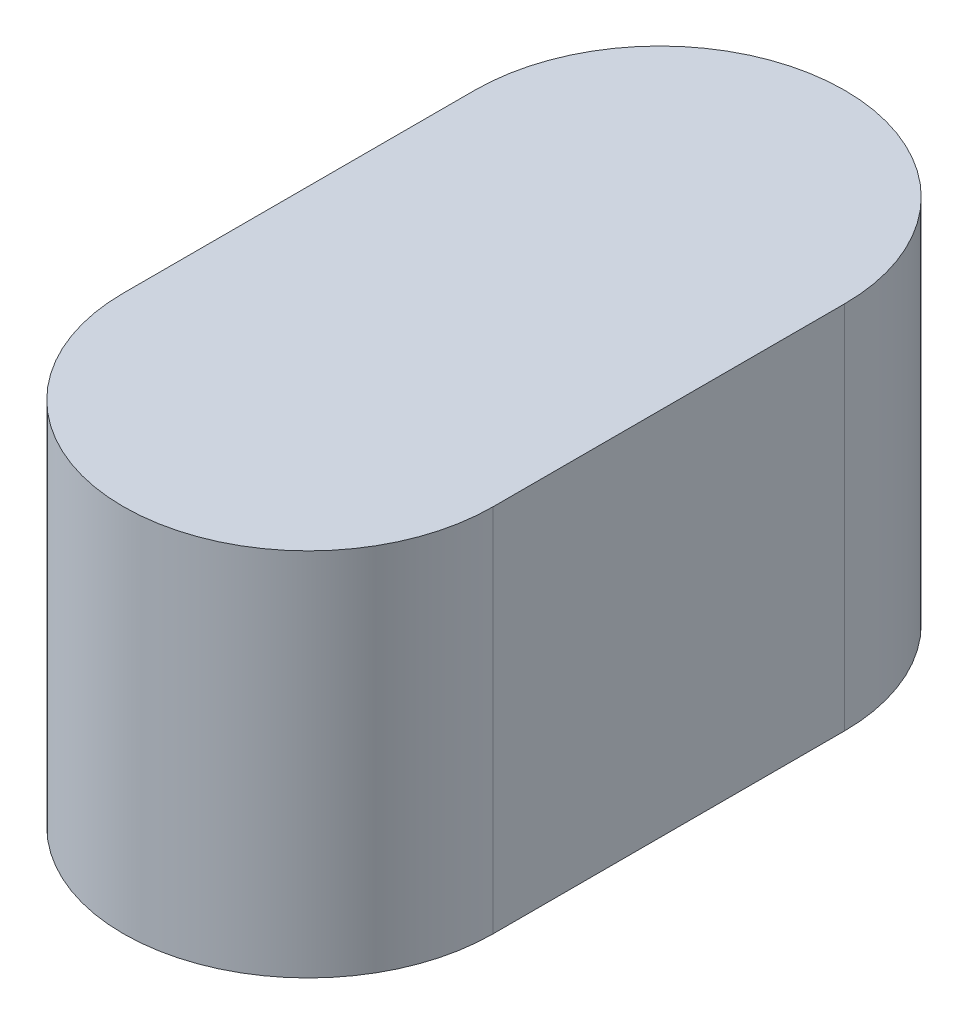
SolidWorks part; units mm, degrees
material "Acier allié"
ref_plane "Plan de face" through (0, 0, 0) normal (0, 0, 1) x (1, 0, 0)
ref_plane "Plan de dessus" through (0, 0, 0) normal (0, 1, 0) x (1, 0, 0)
ref_plane "Plan de droite" through (0, 0, 0) normal (1, 0, 0) x (0, 0, -1)
sketch "Esquisse1" plane through (0, 0, 0) normal (0, 1, 0) x (1, 0, 0)
  line L0 (0, 1.9) -> (0, -1.9) construction
  line L1 (2, 1.9) -> (2, -1.9)
  line L2 (-2, 1.9) -> (-2, -1.9)
  arc A0 (2, 1.9) -> (-2, 1.9) centre (0, 1.9) ccw
  arc A1 (-2, -1.9) -> (2, -1.9) centre (0, -1.9) ccw
  point P2 (0, 0)
  dimension "D2" = 7.8
  dimension "D1" = 4
extrude "Boss.-Extru.1" add sketch "Esquisse1" along normal blind 4
